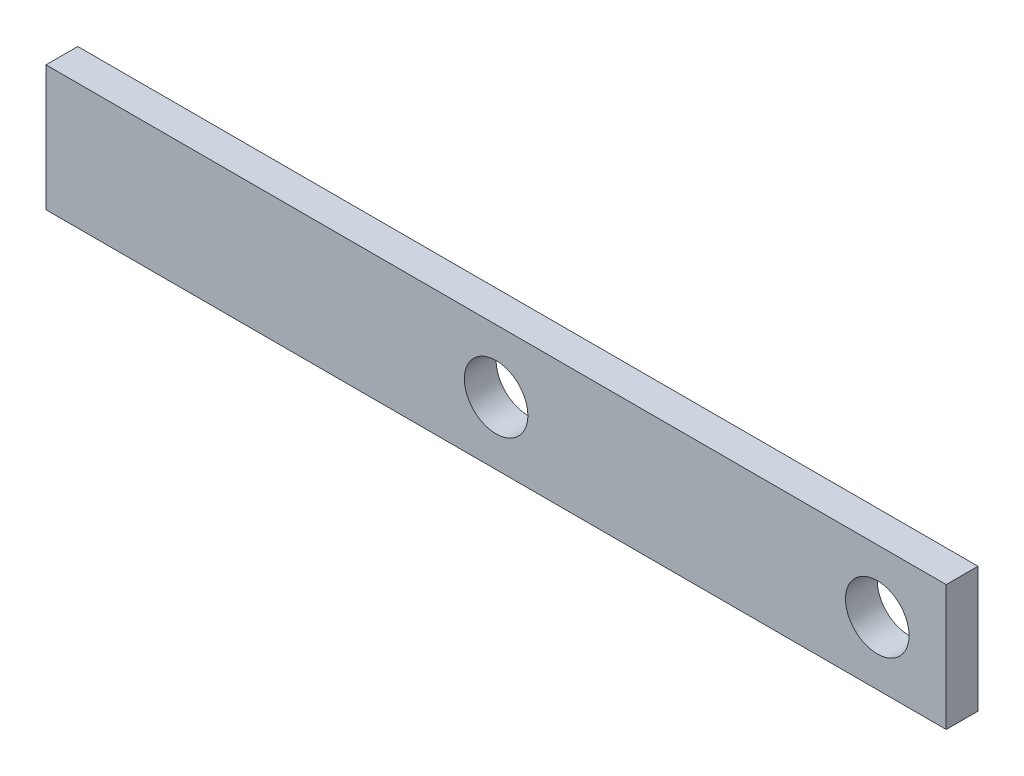
SolidWorks part; units mm, degrees
material "Fundición maleable"
ref_plane "Alzado" through (0, 0, 0) normal (0, 0, 1) x (1, 0, 0)
ref_plane "Planta" through (0, 0, 0) normal (0, 1, 0) x (1, 0, 0)
ref_plane "Vista lateral" through (0, 0, 0) normal (1, 0, 0) x (0, 0, -1)
sketch "Croquis1" plane through (0, 0, 0) normal (0, 0, 1) x (1, 0, 0)
  line L0 (120, 0) -> (-120, 0) construction
  line L2 (-141.7065, 19.7563) -> (141.7065, 19.7563)
  line L3 (-141.7065, 19.7563) -> (-141.7065, -19.7563)
  line L4 (-141.7065, -19.7563) -> (141.7065, -19.7563)
  line L5 (141.7065, 19.7563) -> (141.7065, -19.7563)
  line L6 (-141.7065, 19.7563) -> (141.7065, -19.7563) construction
  line L7 (-141.7065, -19.7563) -> (141.7065, 19.7563) construction
  circle A0 centre (0, 0) radius 10
  circle A1 centre (120, 0) radius 10
  point P4 (0, 0)
  dimension "D2" = 20
  dimension "D3" = 20
  dimension "D1" = 240
extrude "Saliente-Extruir1" add sketch "Croquis1" along normal blind 10
